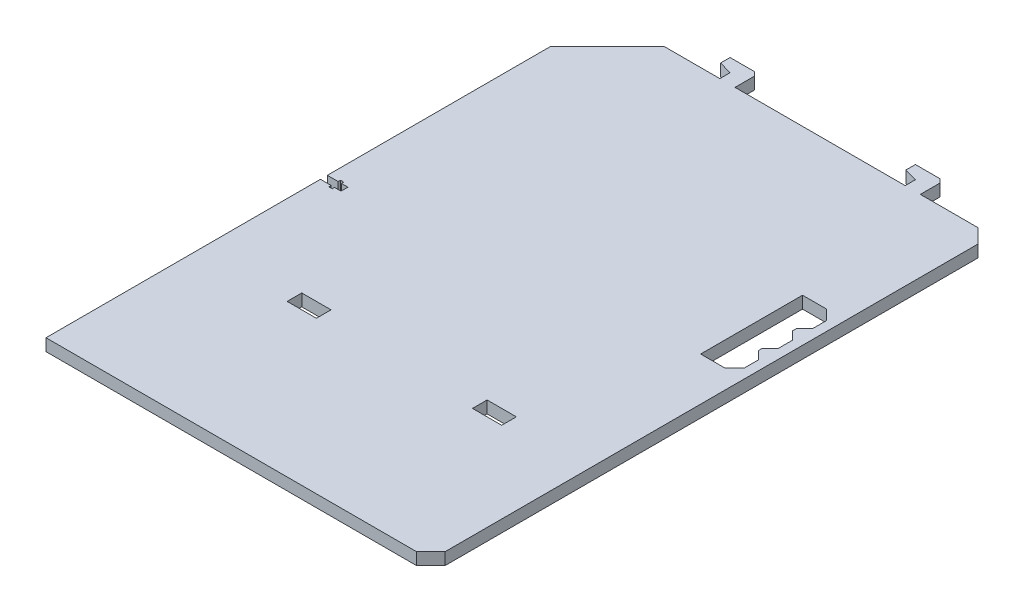
SolidWorks part; units mm, degrees
ref_plane "Front Plane" through (0, 0, 0) normal (0, 0, 1) x (1, 0, 0)
ref_plane "Top Plane" through (0, 0, 0) normal (0, 1, 0) x (1, 0, 0)
ref_plane "Right Plane" through (0, 0, 0) normal (1, 0, 0) x (0, 0, -1)
sketch "Sketch1" plane through (0, 0, 0) normal (0, 1, 0) x (1, 0, 0)
  line L0 (136.176, 177.3) -> (166.73, 177.3)
  line L1 (-29.725, -120.2) -> (166.73, -120.2)
  line L2 (-29.725, -120.2) -> (-29.725, 25.2493)
  line L3 (0.275, 177.3) -> (29.906, 177.3)
  line L4 (174.23, -112.7) -> (174.23, 169.8)
  line L5 (115.73, -39.625) -> (131.23, -39.625)
  line L6 (33, -31.875) -> (33, -39.625)
  line L7 (160.23, 81.8) -> (160.23, 99.8) construction
  line L8 (17.5, -39.625) -> (33, -39.625)
  line L9 (-29.725, 147.3) -> (0.275, 177.3)
  line L10 (115.73, -31.875) -> (131.23, -31.875)
  line L11 (131.23, -31.875) -> (131.23, -39.625)
  line L12 (115.73, -31.875) -> (115.73, -39.625)
  line L13 (-29.725, 28.9007) -> (-24.025, 28.9007)
  line L14 (22.906, 184.69) -> (29.906, 182.7)
  line L15 (37.946, 177.3) -> (128.136, 177.3)
  line L16 (29.906, 182.7) -> (29.906, 177.3)
  line L17 (164.9579, 82.8) -> (164.9579, 80.8)
  line L18 (136.176, 187.6874) -> (136.176, 177.3)
  line L19 (37.946, 187.6874) -> (37.946, 177.3)
  line L20 (35.946, 189.6874) -> (37.946, 187.6874)
  line L21 (128.136, 182.7) -> (128.136, 177.3)
  line L22 (-24.025, 28.9007) -> (-24.025, 30.1507)
  line L23 (-24.025, 30.1507) -> (-22.225, 30.1507)
  line L24 (-22.225, 30.1507) -> (-22.225, 28.9007)
  line L25 (35.946, 189.6874) -> (22.9416, 189.6874)
  line L26 (-22.225, 28.9007) -> (-18.825, 28.9007)
  line L27 (17.5, -31.875) -> (17.5, -39.625)
  line L28 (22.9416, 189.6874) -> (22.906, 184.69)
  line L29 (-18.825, 28.9007) -> (-18.825, 25.2493)
  line L30 (-18.825, 25.2493) -> (-22.225, 25.2493)
  line L31 (166.73, -120.2) -> (174.23, -112.7)
  line L32 (166.73, 177.3) -> (174.23, 169.8)
  line L33 (-22.225, 25.2493) -> (-22.225, 24.0007)
  line L34 (-22.225, 24.0007) -> (-24.025, 24.0007)
  line L35 (121.136, 184.69) -> (128.136, 182.7)
  line L36 (-24.025, 24.0007) -> (-24.025, 25.2493)
  line L37 (134.176, 189.6874) -> (136.176, 187.6874)
  line L38 (121.1716, 189.6874) -> (121.136, 184.69)
  line L39 (-24.025, 25.2493) -> (-29.725, 25.2493)
  line L40 (-29.725, 28.9007) -> (-29.725, 25.2493) construction
  line L41 (134.176, 189.6874) -> (121.1716, 189.6874)
  line L42 (-29.725, 28.9007) -> (-29.725, 147.3)
  line L43 (17.5, -31.875) -> (33, -31.875)
  line L45 (151.23, 99.8) -> (151.23, 45.8)
  line L46 (160.23, 63.8) -> (160.23, 45.8) construction
  line L55 (164.9579, 64.8) -> (164.9579, 62.8)
  line L56 (164.9579, 82.8) -> (169.23, 87.0721)
  line L57 (169.23, 87.0721) -> (169.23, 94.5279)
  line L58 (169.23, 94.5279) -> (163.9579, 99.8)
  line L59 (163.9579, 99.8) -> (151.23, 99.8)
  line L62 (169.23, 69.0721) -> (169.23, 76.5279)
  line L65 (169.23, 76.5279) -> (164.9579, 80.8)
  line L66 (164.9579, 64.8) -> (169.23, 69.0721)
  line L67 (160.23, 63.8) -> (160.23, 81.8) construction
  line L68 (169.23, 51.0721) -> (169.23, 58.5279)
  line L69 (169.23, 58.5279) -> (164.9579, 62.8)
  line L75 (151.23, 45.8) -> (163.9579, 45.8)
  line L76 (163.9579, 45.8) -> (169.23, 51.0721)
  line L81 (160.23, 45.8) -> (160.23, 63.8) construction
  circle A0 centre (160.23, 72.8) radius 9 construction
  circle A2 centre (160.23, 90.8) radius 9 construction
  circle A5 centre (160.23, 54.8) radius 9 construction
  dimension "D1" = 7.75
  dimension "D3" = 7.75
extrude "Boss-Extrude1" add sketch "Sketch1" along normal blind 6.4
